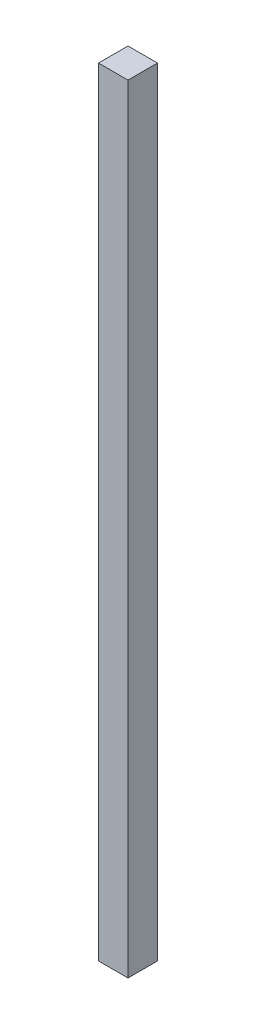
SolidWorks part; units mm, degrees
ref_plane "Front Plane" through (0, 0, 0) normal (0, 0, 1) x (1, 0, 0)
ref_plane "Top Plane" through (0, 0, 0) normal (0, 1, 0) x (1, 0, 0)
ref_plane "Right Plane" through (0, 0, 0) normal (1, 0, 0) x (0, 0, -1)
sketch "Sketch1" plane through (0, 0, 0) normal (0, 1, 0) x (1, 0, 0)
  line L1 (-9.4868, 9.4868) -> (9.4868, 9.4868)
  line L2 (-9.4868, 9.4868) -> (-9.4868, -9.4868)
  line L3 (-9.4868, -9.4868) -> (9.4868, -9.4868)
  line L4 (9.4868, 9.4868) -> (9.4868, -9.4868)
  line L5 (-9.4868, 9.4868) -> (9.4868, -9.4868) construction
  line L6 (-9.4868, -9.4868) -> (9.4868, 9.4868) construction
  point P0 (0, 0)
  dimension "D1" = 18.9737
  dimension "D2" = 18.9737
extrude "Boss-Extrude1" add sketch "Sketch1" along normal blind 500
